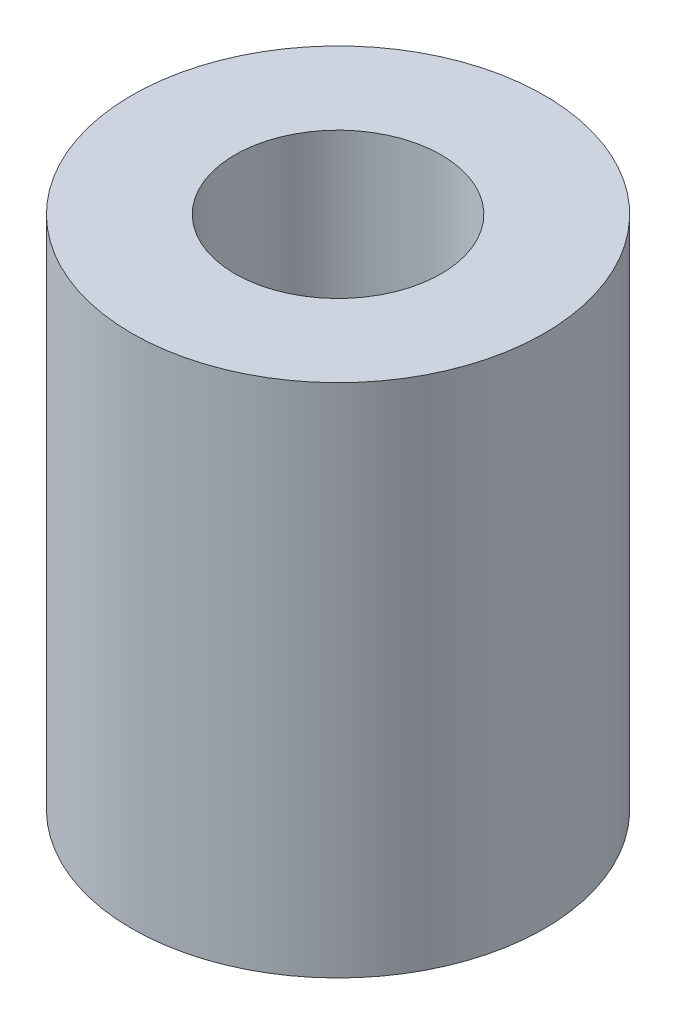
SolidWorks part; units mm, degrees
ref_plane "Front Plane" through (0, 0, 0) normal (0, 0, 1) x (1, 0, 0)
ref_plane "Top Plane" through (0, 0, 0) normal (0, 1, 0) x (1, 0, 0)
ref_plane "Right Plane" through (0, 0, 0) normal (1, 0, 0) x (0, 0, -1)
sketch "Sketch1" plane through (0, 0, 0) normal (0, 1, 0) x (1, 0, 0)
  circle A0 centre (0, 0) radius 10
  circle A1 centre (0, 0) radius 20
extrude "Boss-Extrude1" add sketch "Sketch1" along normal blind 50 contours A1 | A0
